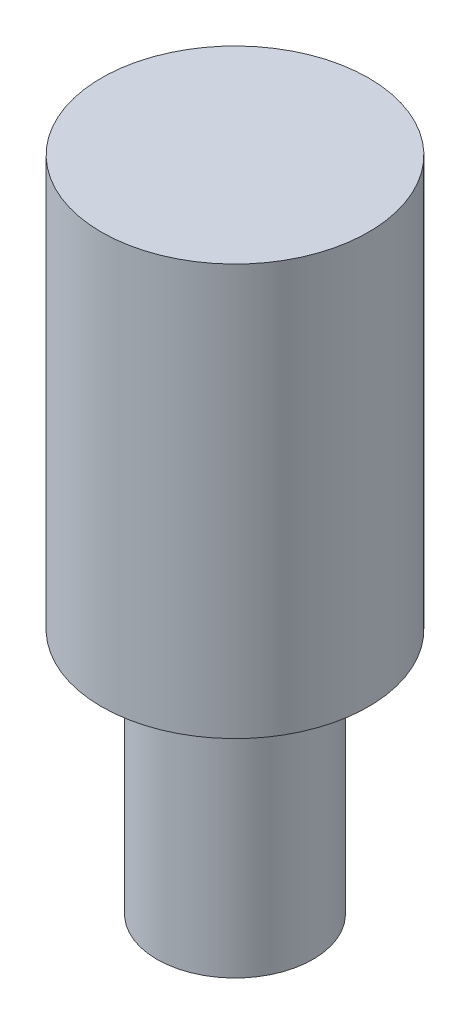
SolidWorks part; units mm, degrees
ref_plane "前视基准面" through (0, 0, 0) normal (0, 0, 1) x (1, 0, 0)
ref_plane "上视基准面" through (0, 0, 0) normal (0, 1, 0) x (1, 0, 0)
ref_plane "右视基准面" through (0, 0, 0) normal (1, 0, 0) x (0, 0, -1)
other "Configuration Table"
sketch "草图1" plane through (0, 0, 0) normal (0, 1, 0) x (1, 0, 0)
  circle A0 centre (0, 0) radius 1.9
  dimension "D1" = 3.8
extrude "凸台-拉伸1" add sketch "草图1" along normal blind 6
sketch "草图2" plane through (0, 6, 0) normal (0, 1, 0) x (1, 0, 0)
  circle A0 centre (0, 0) radius 3.25
  dimension "D1" = 6.5
extrude "凸台-拉伸2" add sketch "草图2" along normal blind 10
